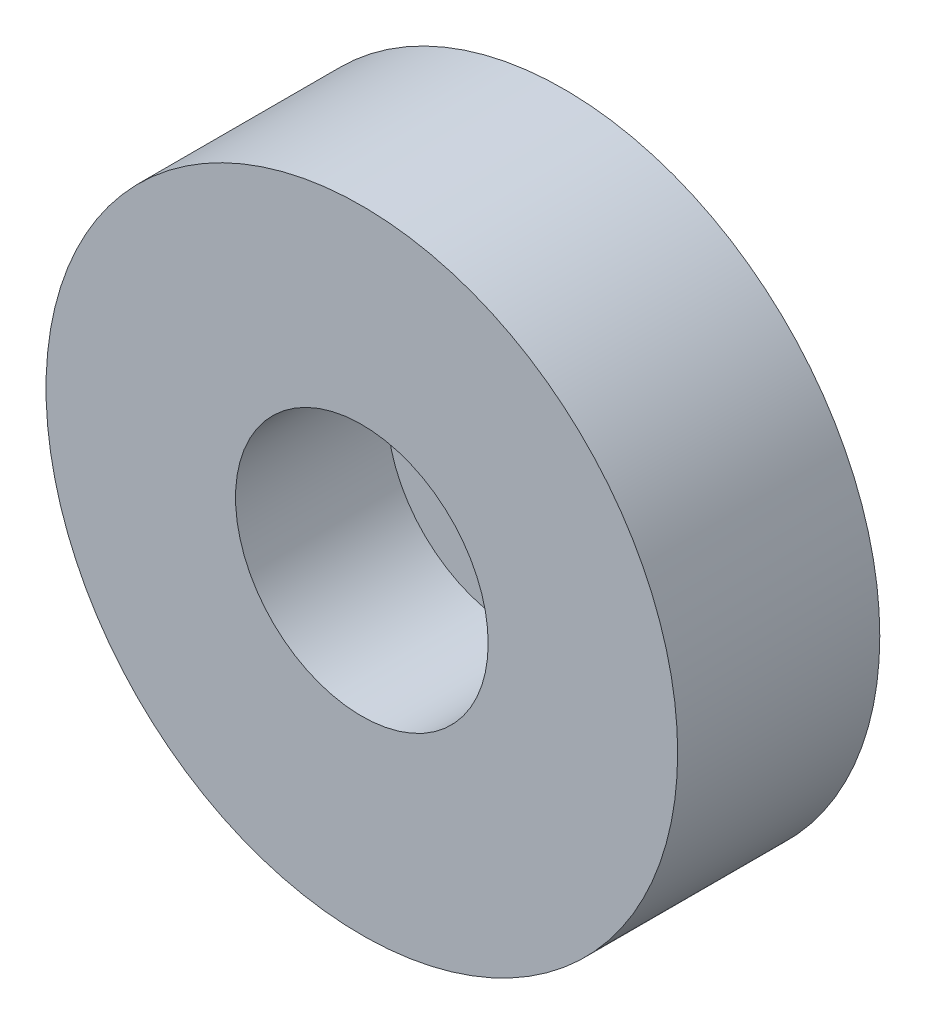
SolidWorks part; units mm, degrees
ref_plane "Front Plane" through (0, 0, 0) normal (0, 0, 1) x (1, 0, 0)
ref_plane "Top Plane" through (0, 0, 0) normal (0, 1, 0) x (1, 0, 0)
ref_plane "Right Plane" through (0, 0, 0) normal (1, 0, 0) x (0, 0, -1)
sketch "Sketch1" plane through (0, 0, 0) normal (0, 0, 1) x (1, 0, 0)
  circle A0 centre (0, 0) radius 12.5
  dimension "D1" = 25
extrude "Boss-Extrude1" add sketch "Sketch1" along normal mid plane 8
sketch "Sketch2" plane through (0, 0, 4) normal (0, 0, 1) x (1, 0, 0)
  circle A1 centre (0, 0) radius 5
  dimension "D1" = 10
extrude "Cut-Extrude1" cut sketch "Sketch2" against normal offset from surface (6 mm away) 2 up to face at (12.5, 0, -4)
sketch "Sketch3" plane through (0, 0, -2) normal (0, 0, 1) x (1, 0, 0)
  circle A0 centre (0, 0) radius 2.25
  dimension "D1" = 4.5
extrude "Cut-Extrude2" cut sketch "Sketch3" against normal up to surface (2 mm away) up to face at (12.5, 0, -4)
